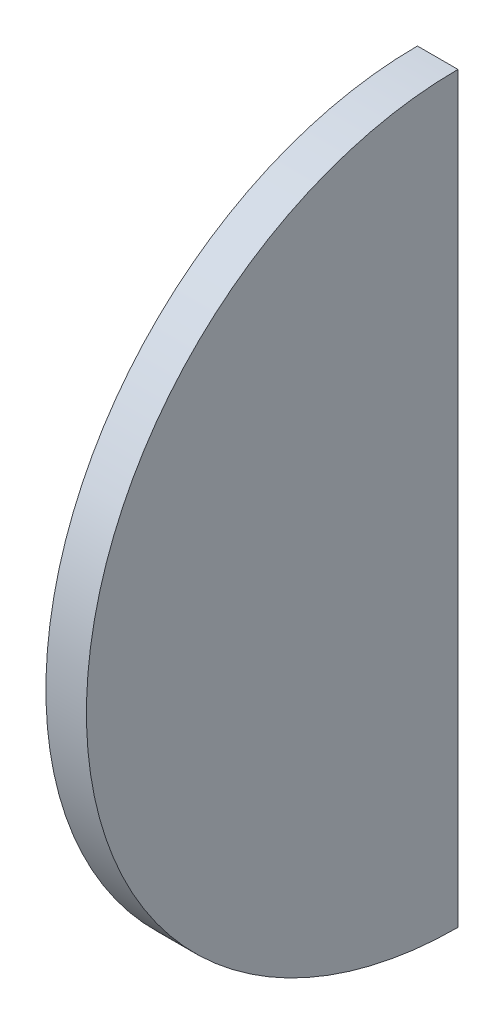
SolidWorks part; units mm, degrees
ref_plane "Front Plane" through (0, 0, 0) normal (0, 0, 1) x (1, 0, 0)
ref_plane "Top Plane" through (0, 0, 0) normal (0, 1, 0) x (1, 0, 0)
ref_plane "Right Plane" through (0, 0, 0) normal (1, 0, 0) x (0, 0, -1)
sketch "Sketch1" plane through (0, 0, 0) normal (1, 0, 0) x (0, 0, -1)
  line L0 (0, 698.5) -> (0, -698.5)
  arc A0 (0, 698.5) -> (0, -698.5) centre (0, 0) ccw
extrude "Boss-Extrude1" add sketch "Sketch1" along normal blind 76.2
